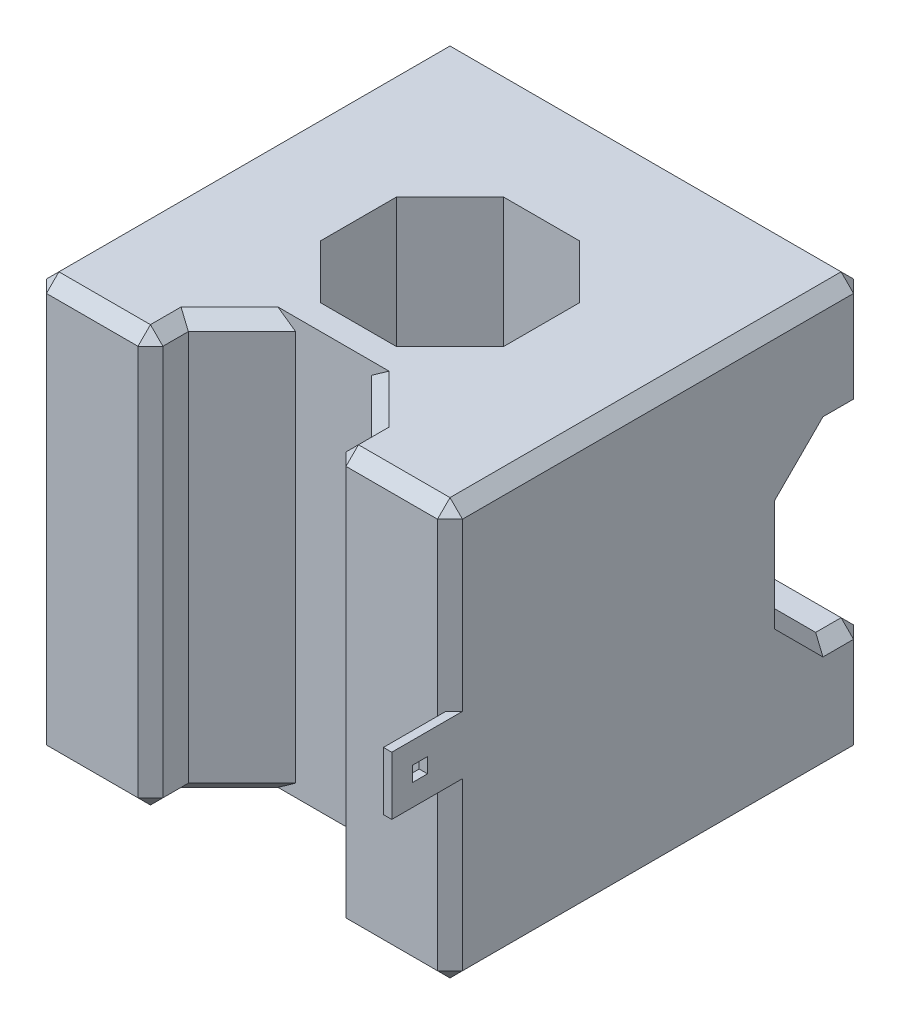
SolidWorks part; units mm, degrees
ref_plane "Front" through (0, 0, 0) normal (0, 0, 1) x (1, 0, 0)
ref_plane "Top" through (0, 0, 0) normal (0, 1, 0) x (1, 0, 0)
ref_plane "Right" through (0, 0, 0) normal (1, 0, 0) x (0, 0, -1)
sketch "Sketch1" plane through (0, 0, 0) normal (0, 0, 1) x (1, 0, 0)
  line L1 (0, 0) -> (50, 0)
  line L2 (0, 0) -> (0, 50)
  line L3 (0, 50) -> (50, 50)
  line L4 (50, 0) -> (50, 50)
  dimension "D1" = 50
extrude "Boss-Extrude1" add sketch "Sketch1" along normal blind 50
sketch "Sketch3" plane through (0, 0, 0) normal (0, -1, 0) x (1, 0, 0)
  line L0 (0, 50) -> (50, 50) construction
  line L1 (25, 25) -> (0, 25) construction
  line L2 (29.5563, 36) -> (20.4437, 36)
  line L3 (20.4437, 36) -> (14, 29.5563)
  line L4 (14, 29.5563) -> (14, 20.4437)
  line L5 (14, 20.4437) -> (20.4437, 14)
  line L6 (20.4437, 14) -> (29.5563, 14)
  line L7 (14, 61) -> (36, 61) construction
  line L8 (14, 61) -> (14, 39) construction
  line L9 (14, 39) -> (36, 39) construction
  line L10 (36, 61) -> (36, 39) construction
  line L11 (14, 61) -> (36, 39) construction
  line L12 (14, 39) -> (36, 61) construction
  line L13 (29.5563, 14) -> (36, 20.4437)
  line L14 (36, 20.4437) -> (36, 29.5563)
  line L15 (36, 29.5563) -> (29.5563, 36)
  line L16 (29.5563, 39) -> (36, 45.4437)
  line L17 (36, 45.4437) -> (36, 54.5563)
  line L18 (36, 54.5563) -> (29.5563, 61)
  line L19 (29.5563, 61) -> (20.4437, 61)
  line L20 (20.4437, 61) -> (14, 54.5563)
  line L21 (14, 54.5563) -> (14, 45.4437)
  line L22 (14, 45.4437) -> (20.4437, 39)
  line L23 (20.4437, 39) -> (29.5563, 39)
  line L24 (0, 50) -> (0, 0) construction
  circle A0 centre (25, 50) radius 11 construction
  circle A1 centre (25, 25) radius 11 construction
  point P5 (25, 50)
  dimension "D1" = 22
extrude "Cut-Extrude2" cut sketch "Sketch3" against normal through all
sketch "Sketch4" plane through (0, 0, 0) normal (-1, 0, 0) x (0, 0, 1)
  line L0 (0, 50) -> (0, 0) construction
  line L1 (4.5563, 14) -> (11, 20.4437)
  line L2 (11, 20.4437) -> (11, 29.5563)
  line L3 (11, 29.5563) -> (4.5563, 36)
  line L4 (4.5563, 36) -> (-4.5563, 36)
  line L5 (-4.5563, 36) -> (-11, 29.5563)
  line L6 (-11, 29.5563) -> (-11, 20.4437)
  line L7 (-11, 20.4437) -> (-4.5563, 14)
  line L8 (-4.5563, 14) -> (4.5563, 14)
  circle A0 centre (0, 25) radius 11 construction
  dimension "D1" = 22
extrude "Cut-Extrude3" cut sketch "Sketch4" against normal through all
chamfer "Chamfer1" distance 1.5 angle 45 36 edges at (50, 32.7782, 7.7782) (0, 32.7782, 7.7782) (0, 36, 2.2782) (0, 17.2218, 7.7782) (0, 7, 0) (0, 14, 2.2782) (25, 14, 0) (0, 43, 0) (0, 50, 25) (17.2218, 50, 42.2218) (14, 50, 47.7218) (32.7782, 50, 42.2218) (36, 50, 47.7218) (25, 50, 0) (50, 36, 2.2782) (25, 36, 0) (50, 43, 0) (50, 17.2218, 7.7782) (50, 14, 2.2782) (50, 7, 0) (32.7782, 0, 42.2218) (36, 0, 47.7218) (43, 0, 50) (50, 50, 25) (36, 25, 50) (43, 50, 50) (50, 25, 50) (50, 0, 25) (25, 0, 0) (0, 0, 25) (17.2218, 0, 42.2218) (14, 0, 47.7218) (7, 50, 50) (14, 25, 50) (7, 0, 50) (0, 25, 50)
sketch "Sketch5" plane through (0, 0, 50) normal (0, 0, 1) x (1, 0, 0)
  line L0 (50, 48.5) -> (50, 1.5) construction
  line L1 (50, 28.5) -> (49, 28.5)
  line L2 (50, 28.5) -> (50, 21.5)
  line L3 (50, 21.5) -> (49, 21.5)
  line L4 (49, 28.5) -> (49, 21.5)
  point P6 (50, 25)
  dimension "D1" = 7
  dimension "D2" = 1
extrude "Boss-Extrude2" add sketch "Sketch5" along normal blind 7 and the other way blind 10
sketch "Sketch6" plane through (50, 0, 0) normal (1, 0, 0) x (0, 0, -1)
  line L0 (-57, 21.5) -> (-57, 28.5) construction
  line L1 (-54.5, 24.1) -> (-52.7, 24.1)
  line L2 (-54.5, 24.1) -> (-54.5, 25.9)
  line L3 (-54.5, 25.9) -> (-52.7, 25.9)
  line L4 (-52.7, 24.1) -> (-52.7, 25.9)
  line L5 (-54.5, 25) -> (-57, 25) construction
  dimension "D1" = 1.8
  dimension "D2" = 2.5
extrude "Cut-Extrude4" cut sketch "Sketch6" against normal blind 7
